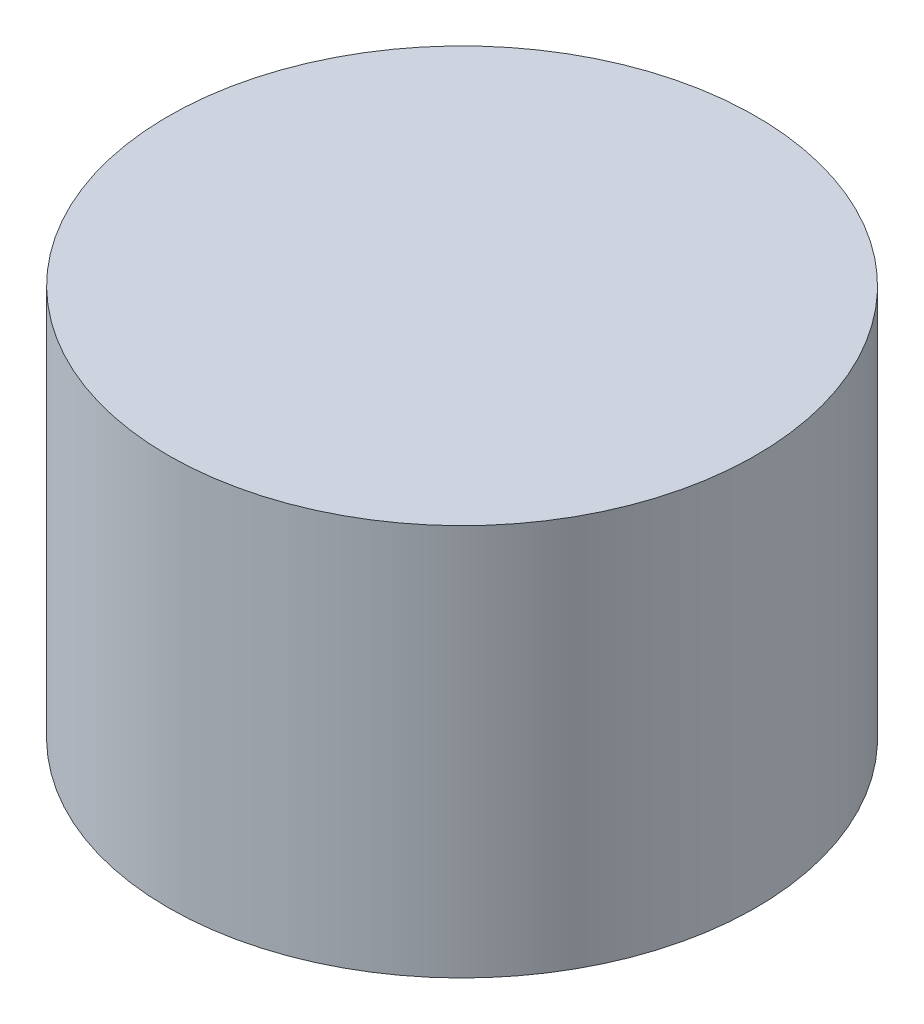
SolidWorks part; units mm, degrees
ref_plane "Front Plane" through (0, 0, 0) normal (0, 0, 1) x (1, 0, 0)
ref_plane "Top Plane" through (0, 0, 0) normal (0, 1, 0) x (1, 0, 0)
ref_plane "Right Plane" through (0, 0, 0) normal (1, 0, 0) x (0, 0, -1)
sketch "Sketch1" plane through (0, 0, 0) normal (0, 1, 0) x (1, 0, 0)
  circle A0 centre (0, 0) radius 38.1
  dimension "D1" = 76.2
extrude "Boss-Extrude1" add sketch "Sketch1" along normal blind 50.8
